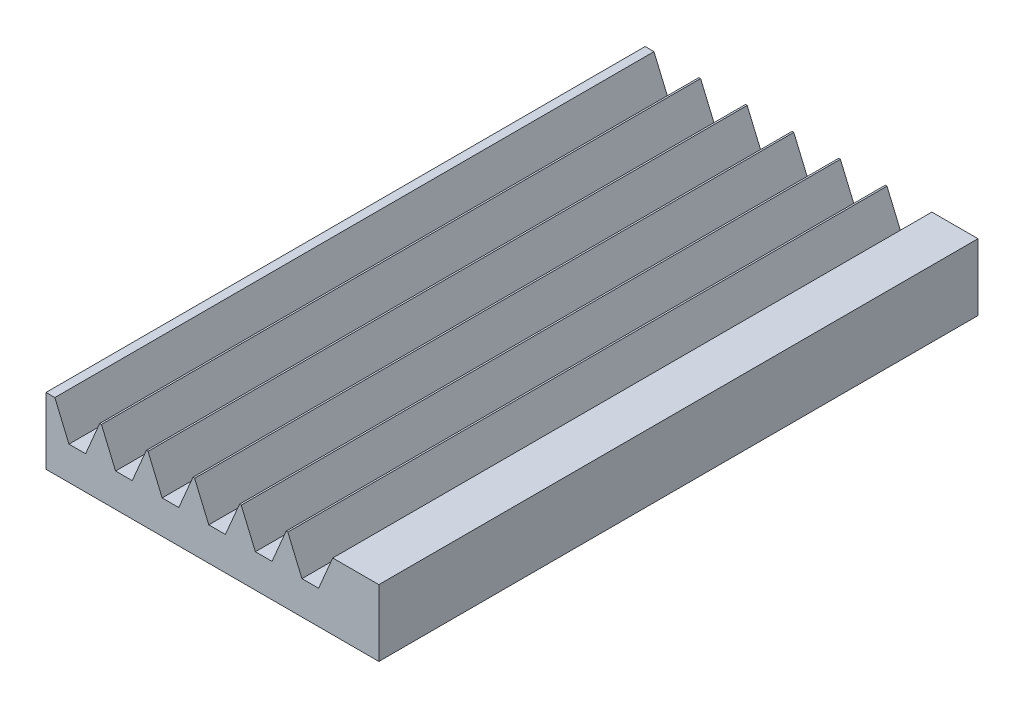
SolidWorks part; units mm, degrees
ref_plane "Front Plane" through (0, 0, 0) normal (0, 0, 1) x (1, 0, 0)
ref_plane "Top Plane" through (0, 0, 0) normal (0, 1, 0) x (1, 0, 0)
ref_plane "Right Plane" through (0, 0, 0) normal (1, 0, 0) x (0, 0, -1)
sketch "Sketch1" plane through (0, 0, 0) normal (0, 0, 1) x (1, 0, 0)
  line L14 (0, 0) -> (10, 0)
  line L15 (0, 0) -> (0, 2)
  line L16 (0, 2) -> (10, 2)
  line L17 (10, 0) -> (10, 2)
  dimension "D1" = 10
  dimension "D2" = 2
extrude "Boss-Extrude1" add sketch "Sketch1" along normal blind 5 and the other way blind 13
sketch "Sketch3" plane through (0, 0, 5) normal (0, 0, 1) x (1, 0, 0)
  line L0 (0.9398, 2) -> (0.9398, 1) construction
  line L1 (10, 2) -> (0, 2) construction
  line L2 (0.6898, 1) -> (1.1898, 1)
  line L3 (0.6898, 1) -> (0.26, 2.0126)
  line L4 (0.26, 2.0126) -> (1.6196, 2.0126)
  line L5 (1.6196, 2.0126) -> (1.1898, 1)
  line L6 (0.9398, 2) -> (0.9398, 2.0126) construction
  point P7 (0.9398, 1)
  dimension "D1" = 1
  dimension "D2" = 0.5
  dimension "D3" = 113
  dimension "D4" = 1.1
extrude "Cut-Extrude1" cut sketch "Sketch3" against normal blind 18
pattern_linear "LPattern2" count 6 spacing 1.4 along (1, 0, 0) of "Cut-Extrude1"
